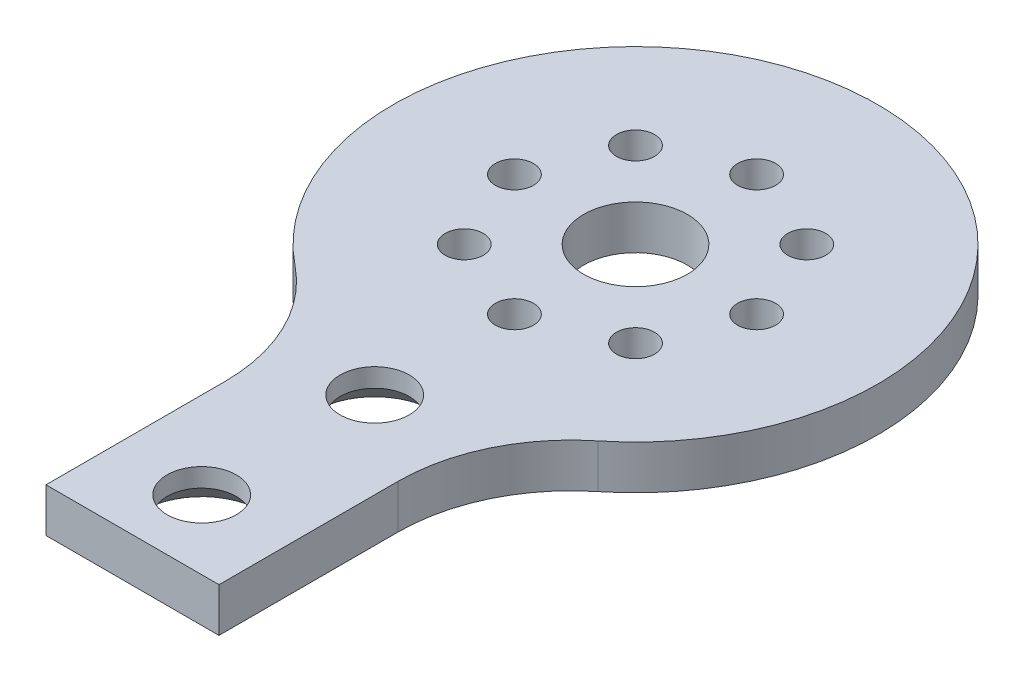
SolidWorks part; units mm, degrees
material "1060 Alloy"
ref_plane "Front Plane" through (0, 0, 0) normal (0, 0, 1) x (1, 0, 0)
ref_plane "Top Plane" through (0, 0, 0) normal (0, 1, 0) x (1, 0, 0)
ref_plane "Right Plane" through (0, 0, 0) normal (1, 0, 0) x (0, 0, -1)
sketch "Sketch1" plane through (0, 0, 0) normal (0, 1, 0) x (1, 0, 0)
  line L0 (-12.5, -72.6917) -> (12.5, -72.6917)
  line L1 (12.5, -72.6917) -> (12.5, -32.6917)
  line L2 (-12.5, -72.6917) -> (-12.5, -32.6917)
  arc A0 (12.5, -32.6917) -> (-12.5, -32.6917) centre (0, 0) ccw
  point P1 (-12.5, -32.6917)
  point P5 (0, -72.6917)
  point P7 (12.5, -53.2582)
  dimension "D2" = 70
  dimension "D1" = 25
  dimension "D3" = 40
extrude "Boss-Extrude1" add sketch "Sketch1" along normal blind 6.35 contours A0 L2 L0 L1
sketch "Sketch2" plane through (0, 0, 0) normal (0, -1, 0) x (1, 0, 0)
  circle A0 centre (0, 0) radius 17.5 construction
  point P3 (17.5, 0)
  point P4 (0, 0)
  point P5 (15.8532, -5.9693)
  point P6 (12.3744, -12.3744)
  point P7 (0, -17.5)
  point P8 (-12.3744, -12.3744)
  point P9 (-17.5, 0)
  point P10 (-12.3744, 12.3744)
  point P11 (0, 17.5)
  point P12 (12.3744, 12.3744)
  point P13 (0, 0)
  point P14 (0, 0)
  point P15 (0, 0)
  dimension "D2" = 35
  dimension "D1" = 8
hole_wizard "M5 Clearance Hole1" positions "Sketch3" profile "Sketch4" hole size "M5" standard "ANSI Metric" end condition through all
sketch "Sketch3" plane through (0, 0, 0) normal (0, -1, 0) x (-1, 0, 0)
  point P0 (0, 17.5)
  point P3 (12.3744, 12.3744)
  point P6 (17.5, 0)
  point P9 (12.3744, -12.3744)
  point P12 (0, -17.5)
  point P15 (-12.3744, -12.3744)
  point P18 (-17.5, 0)
  point P21 (-12.3744, 12.3744)
sketch "Sketch4" plane through (0, 0, -17.5) normal (1, 0, 0) x (0, 0, -1)
  line L0 (0, 0) -> (0, 6.35)
  line L1 (0, 6.35) -> (2.75, 6.35)
  line L2 (2.75, 6.35) -> (2.75, 0.025)
  line L3 (2.75, 0.025) -> (2.775, 0)
  line L5 (2.775, 0) -> (0, 0)
  line L6 (-2.75, 0.025) -> (-2.775, 0) construction
  line L11 (0, -6.35) -> (0, 107.95) construction
  dimension "Thru Hole Dia." = 5.5
  dimension "Thru Hole Depth" = 6.35
  dimension "Near C'Sink Dia." = 5.55
  dimension "Near C'Sink Angle" = 90
sketch "Sketch5" plane through (0, 0, 0) normal (0, -1, 0) x (1, 0, 0)
  circle A0 centre (0, 0) radius 7.5
  dimension "D1" = 15
extrude "Cut-Extrude1" cut sketch "Sketch5" against normal through all
sketch "Sketch6" plane through (0, 0, 0) normal (0, -1, 0) x (1, 0, 0)
  line L0 (0, 72.6917) -> (0, 37.6917) construction
  line L1 (-12.5, 72.6917) -> (12.5, 72.6917) construction
  point P5 (0, 62.6917)
  dimension "D1" = 25
  dimension "D2" = 10
hole_wizard "CSK for M8 Flat Head Machine Screw1" positions "Sketch7" profile "Sketch8" countersink size "M8" standard "ANSI Metric" end condition through all
sketch "Sketch7" plane through (0, 0, 0) normal (0, -1, 0) x (-1, 0, 0)
  point P0 (0, -37.6917)
  point P3 (0, -62.6917)
sketch "Sketch8" plane through (0, 0, 37.6917) normal (1, 0, 0) x (0, 0, -1)
  line L0 (0, 0) -> (0, 6.35)
  line L1 (0, 6.35) -> (5, 6.35)
  line L2 (5, 6.35) -> (5, 3.65)
  line L3 (5, 3.65) -> (8.65, 0)
  line L5 (8.65, 0) -> (0, 0)
  line L6 (-5, 3.65) -> (-8.65, 0) construction
  line L11 (0, -6.35) -> (0, 107.95) construction
  dimension "Thru Hole Dia." = 10
  dimension "Thru Hole Depth" = 6.35
  dimension "Near C'Sink Dia." = 17.3
  dimension "Near C'Sink Angle" = 90
fillet "Fillet1" radius 25 2 edges at (-12.5, 3.175, 32.6917) (12.5, 3.175, 32.6917)
